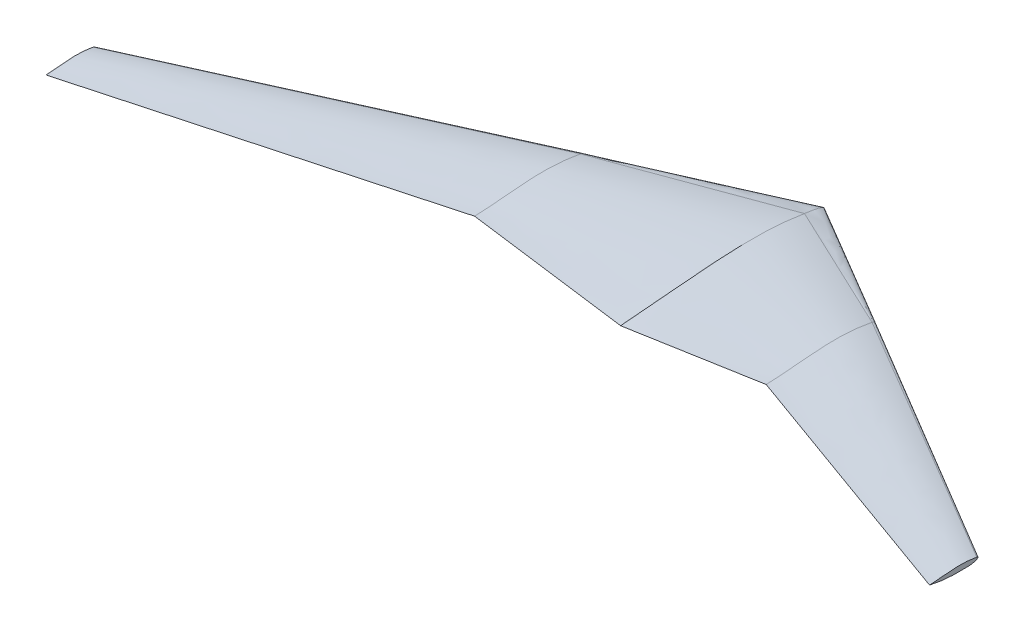
SolidWorks part; units mm, degrees
ref_plane "Front Plane" through (0, 0, 0) normal (0, 0, 1) x (1, 0, 0)
ref_plane "Top Plane" through (0, 0, 0) normal (0, 1, 0) x (1, 0, 0)
ref_plane "Right Plane" through (0, 0, 0) normal (1, 0, 0) x (0, 0, -1)
sketch "Sketch2" plane through (0, 0, 0) normal (0, 1, 0) x (1, 0, 0)
  line L0 (0, -5194.446) -> (0, 1731.482)
  line L1 (0, 0) -> (-18096.1342, 0) construction
  line L2 (0, 0) -> (-22098, -13277.818) construction
  line L3 (-22098, -15095.8741) -> (-22098, -12671.7993)
  line L4 (-22098, -12671.7993) -> (0, 1731.482)
  line L5 (-22098, -15095.8741) -> (0, -5194.446)
  line L6 (-9275.7037, -4314.3398) -> (-9275.7037, -5573.4051) construction
  line L7 (-9275.7037, -5573.4051) -> (-9275.7037, -9350.601) construction
  line L8 (-9275.7037, -5573.4051) -> (0, -5573.4051) construction
  line L9 (0, 346.2964) -> (-6827.52, -3825.6374) construction
  line L10 (0, -29565.6) -> (-7316.724, -34881.5112) construction
  line L11 (0, -29565.6) -> (-8167.6786, -29565.6) construction
  line L12 (0, -28507.0982) -> (0, -32741.1055)
  line L13 (-7316.724, -35992.9378) -> (-7316.724, -34511.0356)
  line L14 (-7316.724, -34511.0356) -> (0, -28507.0982)
  line L15 (0, -32741.1055) -> (-7316.724, -35992.9378)
  line L16 (-2399.2704, -30475.8849) -> (-2399.2704, -31308.772) construction
  line L17 (-2399.2704, -31308.772) -> (-2399.2704, -33807.4331) construction
  line L18 (-2399.2704, -31308.772) -> (0, -31308.772) construction
  line L19 (-6827.52, -3825.6374) -> (-6827.52, -6593.1427) construction
  line L20 (-6827.52, -6593.1427) -> (0, -3116.6676) construction
  line L21 (0, 346.2964) -> (0, -3116.6676) construction
  line L22 (0, -3116.6676) -> (0, 346.2964) construction
  line L23 (0, 346.2964) -> (0, -1385.1856) construction
  line L24 (0, 346.2964) -> (0, -3116.6676) construction
  line L25 (0, -1385.1856) -> (-6827.52, -5209.39) construction
  line L26 (0, 346.2964) -> (-22098, -13156.6142) construction
  line L27 (-3160.776, -1585.0854) -> (-3160.776, -3155.5874) construction
  line L28 (-3160.776, -3155.5874) -> (-3160.776, -4726.0893) construction
  line L29 (-3160.776, -3155.5874) -> (0, -3155.5874) construction
  line L30 (-2429.7983, -1138.4239) -> (-10049.7983, -5794.6)
  line L31 (-10049.7983, -5794.6) -> (-10049.7983, -8233.8805)
  line L32 (-10049.7983, -8233.8805) -> (-2429.7983, -4353.886)
  line L33 (-2429.7983, -1138.4239) -> (-2429.7983, -4353.886)
  line L34 (-5965.4783, -3298.8896) -> (-5965.4783, -6154.2034) construction
  line L35 (-2429.7983, -2746.1549) -> (-10049.7983, -7014.2402) construction
  line L36 (-5965.4783, -4726.5465) -> (0, -4726.5465) construction
  point P44 (0, -4726.0893)
  point P45 (-5804.0658, -4659.0051)
  point P46 (-2429.7983, -1138.4239)
  point P47 (0, -4963.339)
  point P48 (0, 0)
  point P49 (-6291.278, -4909.0322)
  point P50 (-5068.7983, -4224.3015)
  point P51 (-5447.2424, -2982.2233)
  point P52 (0, 0)
  dimension "Wing Sweep" = 31
  dimension "Half Span" = 22098
  dimension "Wing Root" = 6925.928
  dimension "D4" = 1731.482
  dimension "Wing Tip" = 2424.0748
  dimension "D6" = 606.0187
  dimension "Wing YBar" = 9275.7037
  dimension "Tail Sweep" = 36
  dimension "Tail Root" = 4234.0073
  dimension "D10" = 1058.5018
  dimension "Tail Tip" = 1481.9022
  dimension "D12" = 370.4756
  dimension "D13" = 7316.724
  dimension "Tail Ybar" = 2399.2704
  dimension "First Spar" = 1385.1856
  dimension "Second Spar" = 4848.1496
  dimension "Fuel Tip" = 2767.5053
  dimension "Tip Spar" = 484.815
  dimension "Fuel Ybar" = 3160.776
  dimension "Fuel Tank Length" = 6827.52
  dimension "Tail Arm" = 29565.6
  dimension "D3" = 846.8586
  dimension "D5" = 3215.4621
  dimension "D7" = 7620
  dimension "D2" = 3535.68
sketch "Sketch4" plane through (0, 0, 0) normal (0, 1, 0) x (1, 0, 0)
  line L0 (0, 15244.4349) -> (0, -37790.7651) construction
  line L1 (-2240.28, 15244.4349) -> (2240.28, 15244.4349) construction
  line L2 (-2240.28, 8523.5949) -> (-2240.28, -28829.6451)
  line L3 (-2240.28, -37790.7651) -> (2240.28, -37790.7651) construction
  line L4 (2240.28, 8523.5949) -> (2240.28, -28829.6451)
  line L5 (0, -5194.446) -> (0, 1731.482) construction
  line L6 (-9275.7037, -5573.4051) -> (0, -5573.4051) construction
  line L7 (-2399.2704, -31308.772) -> (0, -31308.772) construction
  line L8 (0, 0) -> (-22098, -13277.818) construction
  line L9 (-22098, -12671.7993) -> (0, 1731.482) construction
  line L10 (-8451.85, 1616.4392) -> (-6132.83, 1616.4392)
  line L11 (-8451.85, 1616.4392) -> (-8451.85, -3941.0808)
  line L12 (-8451.85, -3941.0808) -> (-6132.83, -3941.0808)
  line L13 (-6132.83, 1616.4392) -> (-6132.83, -3941.0808)
  line L14 (2240.28, 8523.5949) -> (-2240.28, 8523.5949)
  arc A0 (-2240.28, -28829.6451) -> (2240.28, -28829.6451) centre (0, -28829.6451) ccw construction
  spline S0 degree 2 poles (-2240.28, 8523.5949) (-3493.3317, 12850.6725) (0, 15244.4349) knots 0 0 0 1 1 1 construction
  spline S1 degree 2 poles (2240.28, 8523.5949) (3493.3317, 12850.6725) (0, 15244.4349) knots 0 0 0 1 1 1 construction
  spline S2 degree 3 poles (-2240.28, -28829.6451) (-2085.9319, -24596.8954) (-2150.7047, -30572.2669) (-921.2874, -32754.607) (0, -32741.1055) knots 0 0 0 0 0.731427 1 1 1 1 construction
  spline S3 degree 3 poles (2240.28, -28829.6451) (2085.9319, -24596.8954) (2150.7047, -30572.2669) (921.2874, -32754.607) (0, -32741.1055) knots 0 0 0 0 0.731427 1 1 1 1 construction
  spline S4 degree 2 poles (-2240.28, -28829.6451) (-2598.9168, -25444.3223) (0, -27753.3552) knots 0 0 0 1 1 1
  spline S5 degree 2 poles (2240.28, -28829.6451) (2598.9168, -25444.3223) (0, -27753.3552) knots 0 0 0 1 1 1
  point P6 (0, 8523.5949)
  point P7 (0, -28829.6451)
  point P8 (0, -5573.4051)
  point P15 (0, -31069.9251)
  point P28 (-7292.34, 1616.4392)
  point P29 (-7292.34, -3021.6008)
  point P35 (-7292.34, -4381.6799)
  point P44 (-7292.34, -606.5688)
  dimension "Fuse Length" = 53035.2
  dimension "Fuse Dia" = 4480.56
  dimension "D3" = 6720.84
  dimension "D4" = 8961.12
  dimension "D6" = 7292.34
  dimension "Engine Dia" = 2319.02
  dimension "Engine Length" = 5557.52
  dimension "D9" = 4638.04
  dimension "D10" = 2223.008
  dimension "D11" = 4966.8362
  dimension "D2" = 20817.84
ref_plane "Plane1" through (0, 609.6, 0) normal (0, 1, 0) x (1, 0, 0)
sketch "Sketch10" plane through (0, 0, 0) normal (0, 1, 0) x (1, 0, 0)
  line L0 (-22098, -12671.7993) -> (-2240.28, 271.2873)
  line L1 (-2240.28, 8523.5949) -> (-2240.28, -28829.6451) construction
  line L2 (-22098, -12671.7993) -> (-22098, -15095.8741)
  line L3 (-22098, -15095.8741) -> (-7292.34, -8461.9172)
  line L4 (-7292.34, -8461.9172) -> (-2240.28, -8461.9172)
  line L5 (-22098, -15095.8741) -> (0, -5194.446) construction
  line L6 (-22098, -12671.7993) -> (0, 1731.482) construction
  line L7 (-2240.28, -8461.9172) -> (-2240.28, 271.2873) construction
  line L9 (0, 271.2873) -> (0, -8461.9172)
  line L10 (0, -8461.9172) -> (-2240.28, -8461.9172)
  line L11 (0, -5194.446) -> (0, 1731.482) construction
  line L12 (-2240.28, 271.2873) -> (0, 1731.482)
  line L13 (0, 1731.482) -> (0, 271.2873)
ref_plane "Plane4" through (-792.0687, 0, -1215.2186) normal (0.546, 0, 0.8378) x (0.8378, 0, -0.546)
ref_plane "Plane2" through (-22098, 0, 0) normal (1, 0, 0) x (0, 0, -1)
sketch "Sketch13" plane through (0, 0, 0) normal (1, 0, 0) x (0, 0, -1)
  line L0 (162.7728, -67.9102) -> (699.4395, -67.9102) construction
  line L1 (-5194.446, 0) -> (1731.482, 0) construction
  line L2 (-587.4506, -560.1611) -> (-50.784, -560.1611) construction
  spline S0 degree 3 poles (1731.482, 0) (1706.2202, 59.3683) (1618.6501, 85.2768) (1483.3661, 135.0609) (1201.0635, 200.9855) (941.6694, 217.6766) (744.7336, 260.3873) knots 0 0 0 0 0.167606 0.249459 0.419761 1 1 1 1
  spline S1 degree 3 poles (-8454.5465, 0) (-7986.0297, 52.0117) (-7099.7349, 115.1635) (-4039.0852, 388.883) (-1425.0428, 627.2236) (744.7336, 260.3873) knots 0 0 0 0 0.1533 0.288861 1 1 1 1
  spline S2 degree 3 poles (-8454.5465, 0) (-6774.7944, -408.1485) (-4110.0104, -644.8981) (-1115.3852, -719.9903) (449.105, -593.8733) (1234.2508, -422.4775) (1666.028, -173.2544) (1731.482, 0) knots 0 0 0 0 0.497938 0.767789 0.863745 0.949168 1 1 1 1
ref_plane "Plane3" through (-7292.34, 0, 0) normal (1, 0, 0) x (0, 0, -1)
sketch "Sketch11" plane through (-4881.9987, 0, 1450.5616) normal (-0.546, 0, -0.8378) x (-0.8378, 0, 0.546)
  line L2 (20550.1064, 2939.8573) -> (-5827.462, -558.2104)
  line L3 (-5827.462, -558.2104) -> (-5827.462, 558.2104) construction
  line L4 (20550.1064, 3330.6046) -> (-13808.867, 3330.6046) construction
  line L5 (20550.1064, 2939.8573) -> (20550.1064, 3330.6046) construction
  line L6 (-5827.462, 558.2104) -> (-5827.462, 7888.9301)
  line L7 (-5827.462, 7888.9301) -> (20550.1064, 7888.9301)
  line L9 (20550.1064, -4202.8218) -> (-5827.462, -4202.8218)
  line L11 (20550.1064, 3330.6046) -> (20550.1064, 7888.9301)
  line L12 (-5827.462, -4202.8218) -> (-5827.462, -558.2104)
  line L13 (20550.1064, -4202.8218) -> (20550.1064, 2939.8573)
  line L14 (-5827.462, 558.2104) -> (20550.1064, 3330.6046)
  point P6 (20550.1064, 3135.2309)
  point P7 (-5827.462, 0)
  dimension "D2" = 390.7473
  dimension "D3" = 6
  dimension "D1" = 1116.4209
sketch "Sketch14" plane through (-7292.34, 0, 0) normal (1, 0, 0) x (0, 0, -1)
  line L0 (-3501.0603, -82.1696) -> (-2964.3936, -82.1696) construction
  spline S0 degree 3 poles (-8461.9172, 1103.036) (-8037.1629, 1108.0048) (-7345.9901, 1178.9167) (-6321.6201, 1265.7843) (-4978.676, 1368.3946) (-3895.1043, 1297.4108) (-3166.4538, 1153.1733) knots 0 0 0 0 0.23953 0.39219 0.58054 1 1 1 1
  spline S1 degree 2 poles (-3166.4538, 1153.1733) (-3070.7179, 1148.9229) (-3018.4709, 1076.1901) knots 0 0 0 1 1 1
  spline S2 degree 3 poles (-3018.4709, 1076.1901) (-3043.1137, 1015.3574) (-3142.5967, 939.9461) (-3383.5035, 833.3269) (-3706.7832, 769.8098) (-4160.9117, 728.6104) (-5749.3869, 685.9582) (-7214.6853, 800.9268) (-8461.9172, 1103.036) knots 0 0 0 0 0.034836 0.063802 0.142864 0.210368 0.310373 1 1 1 1
sketch "Sketch12" plane through (-22098, 0, 0) normal (1, 0, 0) x (0, 0, -1)
  line L0 (-7342.0217, 413.0651) -> (-15481.4104, 196.6595) construction
  spline S0 degree 3 poles (-12673.1516, 3135.5827) (-12685.3704, 3105.6002) (-12754.0012, 3047.6338) (-12887.8332, 3010.0156) (-13092.6448, 2976.2419) (-13834.6882, 2959.9271) (-14516.4507, 2991.9561) (-15097.2264, 3135.5827) knots 0 0 0 0 0.038801 0.103252 0.166675 0.290387 1 1 1 1
  spline S1 degree 3 poles (-15097.2264, 3135.5827) (-14661.958, 3150.9618) (-13877.1098, 3278.9985) (-13081.8057, 3231.5242) (-12732.4996, 3162.931) knots 0 0 0 0 0.550659 1 1 1 1
  spline S2 degree 3 poles (-12732.4996, 3162.931) (-12710.7831, 3158.4751) (-12691.0004, 3149.359) (-12673.1516, 3135.5827) knots 0 0 0 0 1 1 1 1
  dimension "D1" = 2424.0748
  dimension "D2" = 259.3618
loft "Loft6" add profiles "Sketch13", "Sketch14"
loft "Loft7" add profiles "Sketch12" section face at (-7292.34, 1110.7998, 4882.2807) section "Sketch12"
mirror "Mirror6" about plane through (0, 0, 0) normal (1, 0, 0) of bodies 127
ref_plane "Plane5" through (0, 762, 0) normal (0, 1, 0) x (1, 0, 0)
sketch "Sketch15" plane through (0, 762, 0) normal (0, 1, 0) x (1, 0, 0)
  circle A0 centre (0, -5573.4051) radius 3174.2375
equation "\"D6@Sketch2\" = \"Wing Tip@Sketch2\" / 4"
equation "\"D4@Sketch2\" = \"Wing Root@Sketch2\" / 4"
equation "\"D10@Sketch2\" = \"Tail Root@Sketch2\" / 4"
equation "\"D12@Sketch2\" = \"Tail Tip@Sketch2\" / 4"
equation "\"D13@Sketch2\"=48.01/2"
equation "\"First Spar@Sketch2\"=0.2 * \"Wing Root@Sketch2\""
equation "\"Second Spar@Sketch2\"   = 0.7 * \"Wing Root@Sketch2\""
equation "\"Tip Spar@Sketch2\"=0.2 * \"Wing Tip@Sketch2\""
equation "\"D3@Sketch4\" = 1.5 * \"Fuse Dia@Sketch4\""
equation "\"D4@Sketch4\" = 2 * \"Fuse Dia@Sketch4\""
equation "\"D6@Sketch4\" = 0.33 * \"Half Span@Sketch2\""
equation "\"D9@Sketch4\" = 2 * \"Engine Dia@Sketch4\""
equation "\"D10@Sketch4\" = 0.40 * \"Engine Length@Sketch4\""
equation "\"D2@Sketch11\"=0.35*\"D1@Sketch11\""
